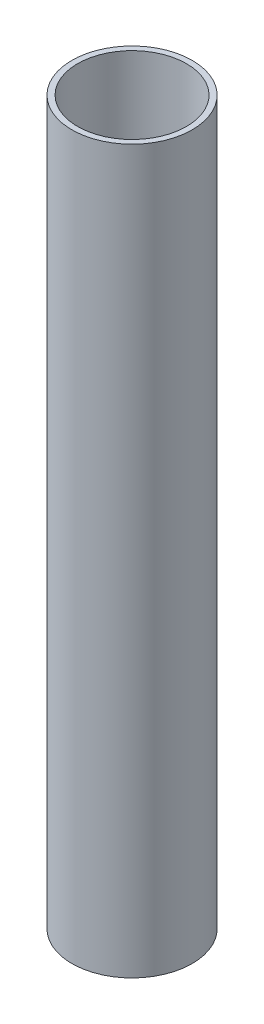
SolidWorks part; units mm, degrees
ref_plane "Front Plane" through (0, 0, 0) normal (0, 0, 1) x (1, 0, 0)
ref_plane "Top Plane" through (0, 0, 0) normal (0, 1, 0) x (1, 0, 0)
ref_plane "Right Plane" through (0, 0, 0) normal (1, 0, 0) x (0, 0, -1)
sketch "Sketch1" plane through (0, 0, 0) normal (0, 1, 0) x (1, 0, 0)
  circle A0 centre (0, 0) radius 25.4
  circle A1 centre (0, 0) radius 22.987
  dimension "D1" = 50.8
  dimension "D2" = 2.413
extrude "Boss-Extrude1" add sketch "Sketch1" along normal blind 304.8
